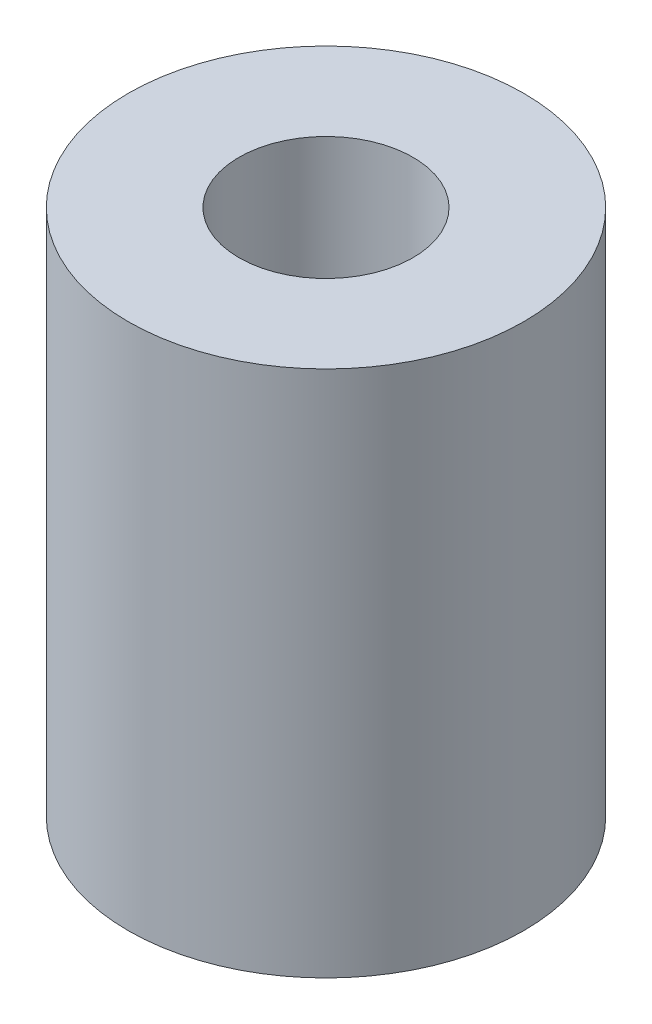
SolidWorks part; units mm, degrees
material "Nylon 101"
ref_plane "Front Plane" through (0, 0, 0) normal (0, 0, 1) x (1, 0, 0)
ref_plane "Top Plane" through (0, 0, 0) normal (0, 1, 0) x (1, 0, 0)
ref_plane "Right Plane" through (0, 0, 0) normal (1, 0, 0) x (0, 0, -1)
other "1/32"
sketch "Sketch1" plane through (0, 0, 0) normal (0, 1, 0) x (1, 0, 0)
  circle A0 centre (0, 0) radius 2.0955
  circle A1 centre (0, 0) radius 4.7625
  dimension "D1" = 4.191
  dimension "D2" = 9.525
extrude "Boss-Extrude1" add sketch "Sketch1" along normal blind 12.7
